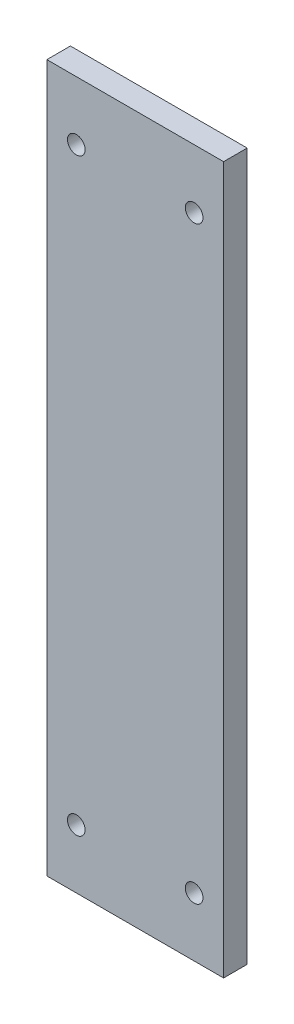
SolidWorks part; units mm, degrees
ref_plane "前视基准面" through (0, 0, 0) normal (0, 0, 1) x (1, 0, 0)
ref_plane "上视基准面" through (0, 0, 0) normal (0, 1, 0) x (1, 0, 0)
ref_plane "右视基准面" through (0, 0, 0) normal (1, 0, 0) x (0, 0, -1)
sketch "草图1" plane through (0, 0, 0) normal (0, 0, 1) x (1, 0, 0)
  line L0 (-24.1925, 53.8432) -> (-24.1925, -66.1568)
  line L1 (-24.1925, -66.1568) -> (5.8075, -66.1568)
  line L2 (5.8075, -66.1568) -> (5.8075, 53.8432)
  line L3 (5.8075, 53.8432) -> (-24.1925, 53.8432)
  line L4 (0.8075, 43.8432) -> (-19.1925, 43.8432) construction
  line L5 (-9.1925, 43.8432) -> (-9.1925, -46.1568) construction
  circle A0 centre (-19.1925, -56.1568) radius 1.5
  circle A1 centre (0.8075, -56.1568) radius 1.5
  circle A2 centre (0.8075, 43.8432) radius 1.5
  circle A3 centre (-19.1925, 43.8432) radius 1.5
  dimension "D1" = 15
  dimension "D2" = 15
extrude "凸台-拉伸1" add sketch "草图1" along normal blind 4
